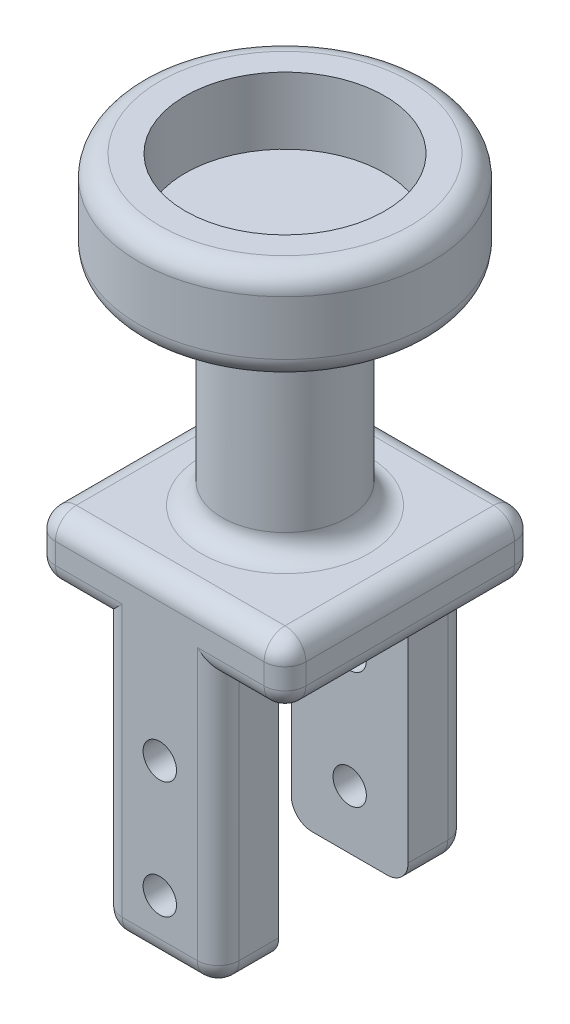
SolidWorks part; units mm, degrees
ref_plane "Front Plane" through (0, 0, 0) normal (0, 0, 1) x (1, 0, 0)
ref_plane "Top Plane" through (0, 0, 0) normal (0, 1, 0) x (1, 0, 0)
ref_plane "Right Plane" through (0, 0, 0) normal (1, 0, 0) x (0, 0, -1)
sketch "Sketch2" plane through (0, 0, 0) normal (0, 1, 0) x (1, 0, 0)
  line L1 (-30, -30) -> (30, -30)
  line L2 (-30, -30) -> (-30, 30)
  line L3 (-30, 30) -> (30, 30)
  line L4 (30, -30) -> (30, 30)
  line L5 (-30, -30) -> (30, 30) construction
  line L6 (-30, 30) -> (30, -30) construction
  point P0 (0, 0)
  dimension "D1" = 60
extrude "Boss-Extrude1" add sketch "Sketch2" along normal blind 15
sketch "Sketch3" plane through (0, 15, 0) normal (0, 1, 0) x (1, 0, 0)
  circle A0 centre (0, 0) radius 15.085
  dimension "D1" = 30.17
extrude "Boss-Extrude2" add sketch "Sketch3" along normal blind 50
sketch "Sketch4" plane through (0, 65, 0) normal (0, 1, 0) x (1, 0, 0)
  circle A0 centre (0, 0) radius 35
  dimension "D1" = 70
extrude "Boss-Extrude3" add sketch "Sketch4" along normal blind 23 contours A0
sketch "Sketch5" plane through (0, 88, 0) normal (0, 1, 0) x (1, 0, 0)
  circle A0 centre (0, 0) radius 23.9
  dimension "D1" = 47.8
extrude "Cut-Extrude1" cut sketch "Sketch5" against normal blind 16
sketch "Sketch8" plane through (0, 0, 0) normal (0, -1, 0) x (1, 0, 0)
  line L0 (0, 0) -> (0, 50000) construction
  line L1 (0, 0) -> (-50000, 0) construction
  line L2 (14, -15.5) -> (-14, -15.5)
  line L3 (14, -15.5) -> (14, -30)
  line L4 (-14, -15.5) -> (-14, -30)
  line L5 (14, -30) -> (-14, -30)
  line L6 (14, -15.5) -> (-14, -30) construction
  line L7 (-14, -15.5) -> (14, -30) construction
  line L8 (30, -30) -> (-30, -30) construction
  line L13 (-14, 15.5) -> (14, 15.5)
  line L14 (-14, 30) -> (14, 30)
  line L15 (14, 15.5) -> (14, 30)
  line L16 (-14, 15.5) -> (-14, 30)
  line L21 (-15.5, -14) -> (-15.5, 14) [skipped]
  line L22 (-15.5, -14) -> (-30, -14) [skipped]
  line L23 (-30, -14) -> (-30, 14) [skipped]
  line L24 (-15.5, 14) -> (-30, 14) [skipped]
  line L25 (15.5, 14) -> (15.5, -14) [skipped]
  line L26 (15.5, 14) -> (30, 14) [skipped]
  line L27 (15.5, -14) -> (30, -14) [skipped]
  line L28 (30, 14) -> (30, -14) [skipped]
  line L29 (-30, 30) -> (30, 30) construction
  point P6 (0, -22.75)
  point P27 (0, 0)
  dimension "D1" = 14.5
  dimension "D2" = 28
  dimension "D3" = 4
extrude "Boss-Extrude4" add sketch "Sketch8" along normal blind 65
sketch "Sketch9" plane through (0, 0, -30) normal (0, 0, -1) x (-1, 0, 0)
  line L0 (14, -65) -> (-14, -65) construction
  circle A0 centre (0, -51) radius 4
  circle A1 centre (0, -23) radius 4
  dimension "D1" = 8
  dimension "D2" = 14
  dimension "D3" = 28
extrude "Cut-Extrude2" cut sketch "Sketch9" against normal blind 65
fillet "Fillet1" radius 5 23 edges at (-30, 15, 0) (14, -65, 22.75) (-14, -65, 22.75) (-14, -65, -22.75) (14, -65, -22.75) (0, -65, -30) (-30, 0, 0) (-30, 7.5, 30) (0, -65, 30) (-22, 0, 30) (-14, -32.5, 30) (14, -32.5, 30) (22, 0, 30) (0, 15, 30) (30, 7.5, 30) (30, 0, 0) (14, -32.5, -30) (-14, -32.5, -30) (-22, 0, -30) (22, 0, -30) (30, 15, 0) (30, 7.5, -30) (0, 15, -30)
fillet "Fillet2" radius 5 4 edges at (0, 88, 35) (0, 65, 35) (0, 65, 15.085) (0, 15, 15.085)
